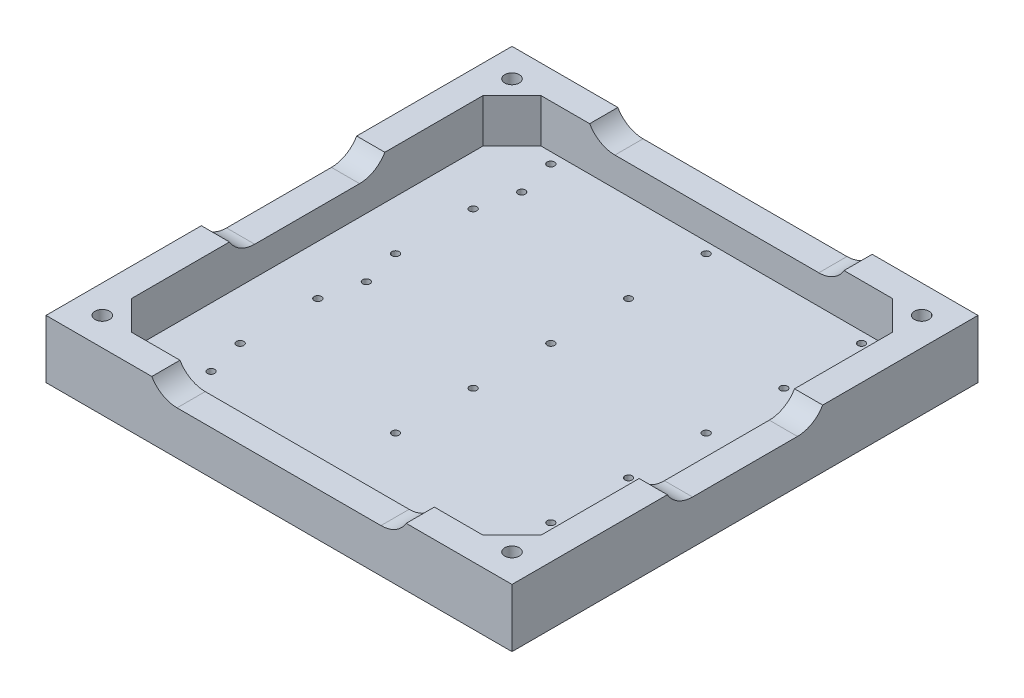
SolidWorks part; units mm, degrees
ref_plane "Front Plane" through (0, 0, 0) normal (0, 0, 1) x (1, 0, 0)
ref_plane "Top Plane" through (0, 0, 0) normal (0, 1, 0) x (1, 0, 0)
ref_plane "Right Plane" through (0, 0, 0) normal (1, 0, 0) x (0, 0, -1)
sketch "Sketch1" plane through (0, 0, 0) normal (0, 1, 0) x (1, 0, 0)
  line L0 (-31.25, 0) -> (-0.75, 0) construction
  line L1 (0.75, 0) -> (31.25, 0) construction
  line L2 (0, 0.75) -> (0, 8) construction
  line L3 (-48, 8) -> (48, 8)
  line L4 (-48, 8) -> (-48, -88)
  line L5 (-48, -88) -> (48, -88)
  line L6 (48, 8) -> (48, -88)
  line L7 (32.75, 0) -> (48, 0) construction
  line L8 (0, -80.75) -> (0, -88) construction
  line L9 (0, -0.75) -> (0, -15.25) construction
  circle A0 centre (0, 0) radius 0.75
  circle A1 centre (32, 0) radius 0.75
  circle A2 centre (-32, 0) radius 0.75
  circle A3 centre (0, -16) radius 0.75
  circle A4 centre (-32, -16) radius 0.75
  circle A5 centre (32, -16) radius 0.75
  circle A6 centre (0, -32) radius 0.75
  circle A7 centre (-32, -32) radius 0.75
  circle A8 centre (32, -32) radius 0.75
  circle A9 centre (0, -48) radius 0.75
  circle A10 centre (-32, -48) radius 0.75
  circle A11 centre (32, -48) radius 0.75
  circle A12 centre (0, -64) radius 0.75
  circle A13 centre (-32, -64) radius 0.75
  circle A14 centre (32, -64) radius 0.75
  circle A15 centre (0, -80) radius 0.75
  circle A16 centre (-32, -80) radius 0.75
  circle A17 centre (32, -80) radius 0.75
  point P19 (0, -88)
  dimension "D1" = 1.5
  dimension "D2" = 8
  dimension "D3" = 16
  dimension "D4" = 30.5
  dimension "D6" = 14.5
  dimension "D5" = 6
extrude "Boss-Extrude1" add sketch "Sketch1" along normal blind 3
sketch "Sketch2" plane through (0, 3, 0) normal (0, 1, 0) x (1, 0, 0)
  line L0 (-36.2, 2.2) -> (36.2, 2.2)
  line L1 (-48, 8) -> (48, 8)
  line L2 (-48, 8) -> (-48, -88)
  line L3 (-48, -88) -> (48, -88)
  line L4 (48, 8) -> (48, -88)
  line L5 (42.2, -3.8) -> (42.2, -76.2)
  line L6 (-36.2, -82.2) -> (36.2, -82.2)
  line L7 (-42.2, -3.8) -> (-42.2, -76.2)
  line L8 (-42.2, 2.2) -> (42.2, 2.2) construction
  line L9 (-42.2, 2.2) -> (-42.2, -82.2) construction
  line L10 (-42.2, -3.8) -> (-36.2, 2.2)
  line L11 (42.2, 2.2) -> (42.2, -82.2) construction
  line L12 (36.2, 2.2) -> (42.2, -3.8)
  line L13 (-42.2, -82.2) -> (42.2, -82.2) construction
  line L14 (42.2, -76.2) -> (36.2, -82.2)
  line L15 (-42.2, -76.2) -> (-36.2, -82.2)
  line L16 (-48, -88) -> (48, -88) construction
  circle A1 centre (32, -80) radius 0.75 construction
  dimension "D2" = 6
  dimension "D3" = 6
  dimension "D4" = 6
  dimension "D5" = 16
  dimension "D1" = 5.8
extrude "Boss-Extrude2" add sketch "Sketch2" along normal blind 9
sketch "Sketch3" plane through (0, 12, 0) normal (0, 1, 0) x (1, 0, 0)
  line L0 (-42.2, 2.2) -> (-39.2, -0.8) construction
  line L1 (-36.2, 2.2) -> (-42.2, -3.8) construction
  line L2 (-36.2, 2.2) -> (-42.2, -3.8) construction
  line L3 (39.2, -0.8) -> (42.2, 2.2) construction
  line L4 (42.2, -3.8) -> (36.2, 2.2) construction
  line L5 (39.2, -79.2) -> (42.2, -82.2) construction
  line L6 (36.2, -82.2) -> (42.2, -76.2) construction
  line L7 (-39.2, -79.2) -> (-42.2, -82.2) construction
  line L8 (-42.2, -76.2) -> (-36.2, -82.2) construction
  line L9 (-42.2, -76.2) -> (-36.2, -82.2) construction
  line L10 (-36.2, -82.2) -> (36.2, -82.2) construction
  line L11 (-42.2, 2.2) -> (42.2, 2.2) construction
  line L12 (-42.2, 2.2) -> (-42.2, -82.2) construction
  line L13 (-42.2, -82.2) -> (42.2, -82.2) construction
  line L14 (42.2, 2.2) -> (42.2, -82.2) construction
  circle A0 centre (-42.2, 2.2) radius 1.5
  circle A1 centre (42.2, 2.2) radius 1.5
  circle A2 centre (42.2, -82.2) radius 1.5
  circle A3 centre (-42.2, -82.2) radius 1.5
  dimension "D1" = 3
extrude "Cut-Extrude1" cut sketch "Sketch3" against normal up to surface (9 mm away) up to face at (0, 3, 40)
sketch "Sketch4" plane through (0, 0, 88) normal (0, 0, 1) x (1, 0, 0)
  line L0 (-26.2, 12) -> (26.2, 12)
  line L2 (-21.0038, 9) -> (21.0038, 9)
  line L5 (-48, 12) -> (48, 12) construction
  arc A0 (-26.2, 12) -> (-21.0038, 9) centre (-21.0038, 15) ccw
  arc A1 (21.0038, 9) -> (26.2, 12) centre (21.0038, 15) ccw
  point P13 (0, 12)
  point P17 (0, 12)
  dimension "D1" = 6
  dimension "D2" = 3
  dimension "D3" = 10
extrude "Cut-Extrude2" cut sketch "Sketch4" against normal through all
sketch "Sketch5" plane through (-48, 0, 0) normal (-1, 0, 0) x (0, 0, 1)
  line L0 (-8, 12) -> (88, 12) construction
  line L1 (29.1962, 9) -> (50.8038, 9)
  line L2 (24, 12) -> (56, 12)
  line L3 (40, 9) -> (40, 0) construction
  line L4 (-8, 0) -> (88, 0) construction
  arc A0 (24, 12) -> (29.1962, 9) centre (29.1962, 15) ccw
  arc A1 (56, 12) -> (50.8038, 9) centre (50.8038, 15) cw
  point P8 (40, 9)
  point P9 (40, 12)
  dimension "D2" = 6
  dimension "D1" = 32
  dimension "D3" = 3
extrude "Cut-Extrude3" cut sketch "Sketch5" against normal through all
sketch "Sketch6" plane through (0, 3, 0) normal (0, 1, 0) x (1, 0, 0)
  line L0 (-31.25, -64) -> (-31.25, -72) construction
  line L1 (-31.25, -72) -> (-30.75, -72) construction
  line L2 (-32, -64) -> (-31.25, -64) construction
  circle A0 centre (-30, -72) radius 0.75
  circle A1 centre (-32, -64) radius 0.75 construction
  dimension "D1" = 8
  dimension "D2" = 0.5
extrude "Cut-Extrude4" cut sketch "Sketch6" against normal through all
pattern_linear "LPattern4" count 3 spacing 32 along (0, 0, -1) of "Cut-Extrude4"
ref_plane "Plane1" through (0, 0, 40) normal (0, 0, -1) x (-1, 0, 0)
